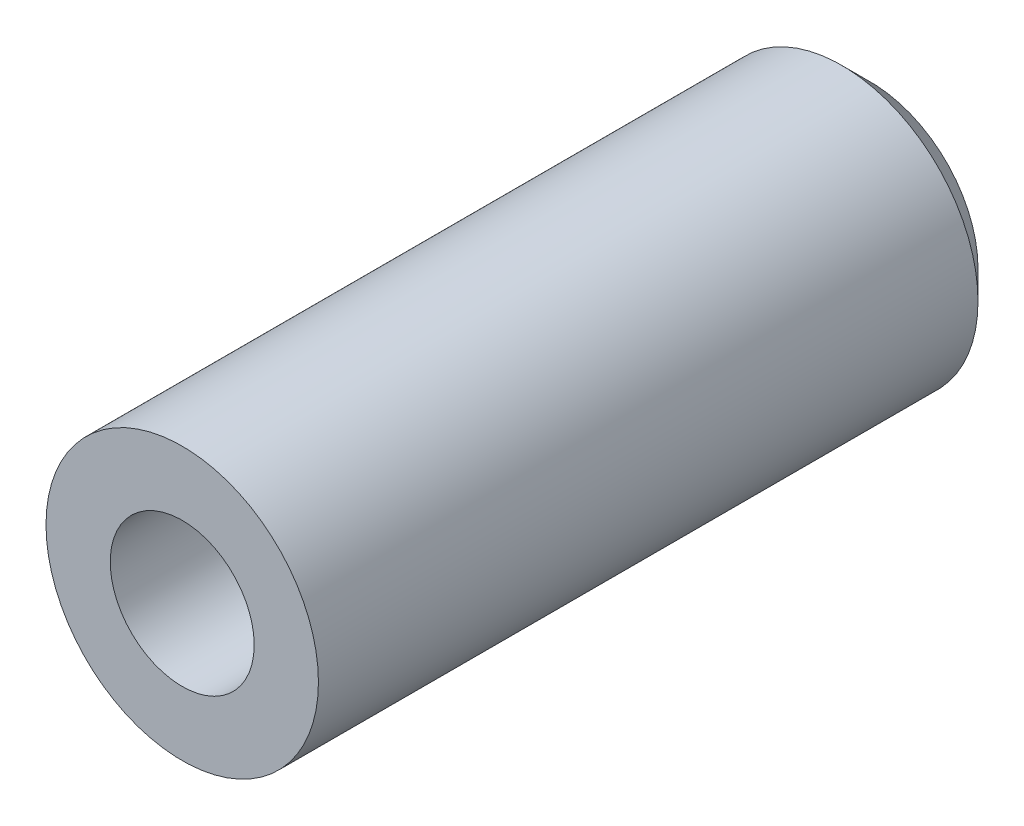
SolidWorks part; units mm, degrees
ref_plane "Front Plane" through (0, 0, 0) normal (0, 0, 1) x (1, 0, 0)
ref_plane "Top Plane" through (0, 0, 0) normal (0, 1, 0) x (1, 0, 0)
ref_plane "Right Plane" through (0, 0, 0) normal (1, 0, 0) x (0, 0, -1)
sketch "Sketch3" plane through (0, 0, 0) normal (0, 1, 0) x (1, 0, 0)
  line L0 (1.255, 0) -> (1.255, 12)
  line L1 (1.255, 12) -> (1.875, 12)
  line L2 (2.375, 11.5) -> (2.375, 0)
  line L3 (2.375, 0) -> (1.255, 0)
  line L4 (0, 0) -> (0, 12) construction
  line L5 (1.875, 12) -> (2.375, 11.5)
  point P3 (2.375, 12)
  point P7 (0, 0)
  point P8 (0, 0)
  dimension "D1" = 12
  dimension "D2" = 4.75
  dimension "D3" = 2.51
revolve "Revolve1" add sketch "Sketch3" angle 360 about L4
